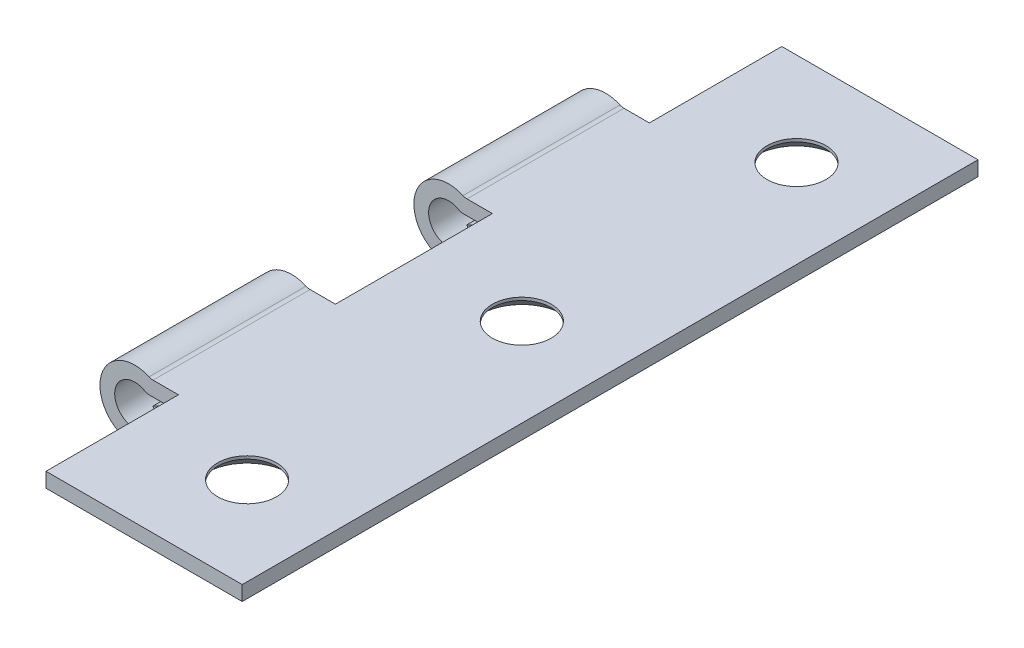
SolidWorks part; units mm, degrees
material "Plain Carbon Steel"
ref_plane "Front Plane" through (0, 0, 0) normal (0, 0, 1) x (1, 0, 0)
ref_plane "Top Plane" through (0, 0, 0) normal (0, 1, 0) x (1, 0, 0)
ref_plane "Right Plane" through (0, 0, 0) normal (1, 0, 0) x (0, 0, -1)
sketch "Sketch1" plane through (0, 0, 0) normal (0, 0, 1) x (1, 0, 0)
  line L0 (1.8655, 3.15) -> (24.45, 3.15)
  line L1 (1.51, 1.65) -> (24.45, 1.65)
  line L2 (3.2174, 1.5003) -> (1.8579, 0.8664)
  line L3 (1.8579, 0.8664) -> (0, 0) construction
  line L4 (0, 0) -> (2.872, 0) construction
  line L5 (24.45, 3.15) -> (24.45, 1.65)
  arc A0 (1.0149, 1.7811) -> (1.8579, 0.8664) centre (0, 0) ccw
  arc A1 (1.4555, 3.2379) -> (3.2174, 1.5003) centre (0, 0) ccw
  arc A2 (1.8655, 3.15) -> (1.4555, 3.2379) centre (1.8655, 4.15) cw
  arc A3 (1.51, 1.65) -> (1.0149, 1.7811) centre (1.51, 2.65) cw
  dimension "D1" = 7.1
  dimension "D2" = 1.5
  dimension "D5" = 1
  dimension "D7" = 28
  dimension "D3" = 1.5
  dimension "D4" = 5.2
  dimension "D6" = 25
extrude "Boss-Extrude1" add sketch "Sketch1" along normal mid plane 75
sketch "Sketch2" plane through (0, 1.65, 0) normal (0, -1, 0) x (1, 0, 0)
  line L0 (-3.55, 37.5) -> (-3.55, -37.5) construction
  line L1 (-3.55, 8) -> (4.45, 8)
  line L2 (-3.55, 8) -> (-3.55, -8)
  line L3 (-3.55, -8) -> (4.45, -8)
  line L4 (4.45, 8) -> (4.45, -8)
  line L5 (24.45, 37.5) -> (24.45, -37.5) construction
  point P4 (4.45, 0)
  dimension "D1" = 20
  dimension "D2" = 16
extrude "Cut-Extrude1" cut sketch "Sketch2" against normal through all both and the other way through all
sketch "Sketch3" plane through (0, 1.65, 0) normal (0, -1, 0) x (1, 0, 0)
  line L0 (4.45, 8) -> (4.45, -8) construction
  line L1 (-3.55, 37.5) -> (4.45, 37.5)
  line L2 (-3.55, 37.5) -> (-3.55, 24)
  line L3 (-3.55, 24) -> (4.45, 24)
  line L4 (4.45, 37.5) -> (4.45, 24)
  line L5 (-3.55, -24) -> (4.45, -24)
  line L6 (-3.55, -24) -> (-3.55, -37.5)
  line L7 (-3.55, -37.5) -> (4.45, -37.5)
  line L8 (4.45, -24) -> (4.45, -37.5)
  line L9 (3.55, -8) -> (-3.55, -8) construction
  line L10 (-3.55, 8) -> (3.55, 8) construction
  line L11 (1.51, 37.5) -> (24.45, 37.5) construction
  line L12 (1.51, -37.5) -> (24.45, -37.5) construction
  line L13 (-3.55, -8) -> (-3.55, -37.5) construction
  point P14 (0, 8)
  dimension "D1" = 16
  dimension "D2" = 16
extrude "Cut-Extrude2" cut sketch "Sketch3" against normal through all both and the other way through all
sketch "Sketch4" plane through (0, 1.65, 0) normal (0, -1, 0) x (1, 0, 0)
  line L0 (24.45, 37.5) -> (24.45, -37.5) construction
  circle A0 centre (15.45, 0) radius 3
  dimension "D1" = 6
  dimension "D2" = 9
extrude "Cut-Extrude3" cut sketch "Sketch4" against normal through all
pattern_linear "LPattern1" count 2 spacing 28 along (0, 0, -1) of "Cut-Extrude3"
mirror "Mirror1" about plane through (0, 0, 0) normal (0, 0, 1) of "LPattern1"
chamfer "Chamfer1" distance 1.2 angle 45 3 edges at (15.45, 1.65, -31) (15.45, 1.65, -3) (15.45, 1.65, 31)
